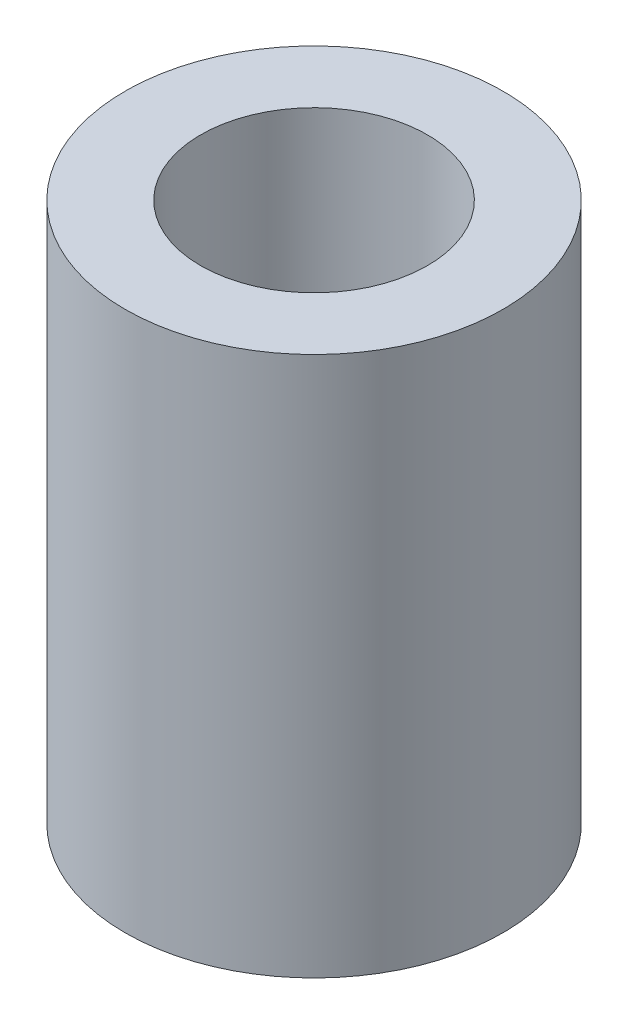
SolidWorks part; units mm, degrees
ref_plane "Front Plane" through (0, 0, 0) normal (0, 0, 1) x (1, 0, 0)
ref_plane "Top Plane" through (0, 0, 0) normal (0, 1, 0) x (1, 0, 0)
ref_plane "Right Plane" through (0, 0, 0) normal (1, 0, 0) x (0, 0, -1)
sketch "Sketch1" plane through (0, 0, 0) normal (0, 1, 0) x (1, 0, 0)
  circle A0 centre (0, 0) radius 3.5
  circle A1 centre (0, 0) radius 2.1
extrude "Boss-Extrude1" add sketch "Sketch1" along normal blind 10
